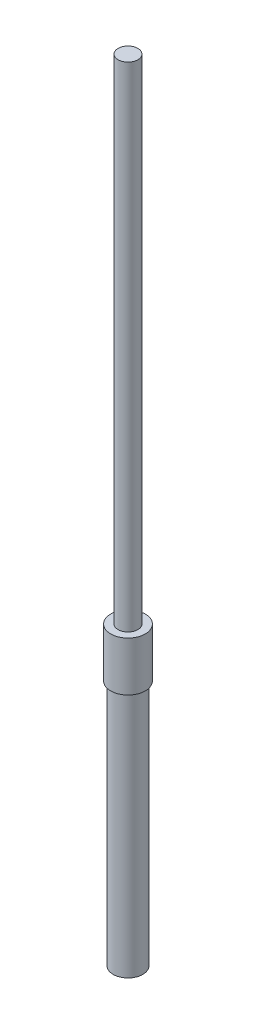
SolidWorks part; units mm, degrees
ref_plane "Front Plane" through (0, 0, 0) normal (0, 0, 1) x (1, 0, 0)
ref_plane "Top Plane" through (0, 0, 0) normal (0, 1, 0) x (1, 0, 0)
ref_plane "Right Plane" through (0, 0, 0) normal (1, 0, 0) x (0, 0, -1)
other "Configuration Table"
sketch "Sketch1" plane through (0, 0, 0) normal (0, 1, 0) x (1, 0, 0)
  circle A0 centre (0, 0) radius 3
  dimension "D1" = 6
extrude "Steel_Tube" add sketch "Sketch1" along normal blind 50
sketch "Sketch2" plane through (0, 0, 0) normal (0, 1, 0) x (1, 0, 0)
  circle A0 centre (0, 0) radius 3.5
extrude "Heatshrink" add sketch "Sketch2" along normal blind 10 from offset 50
sketch "Sketch3" plane through (0, 0, 0) normal (0, 1, 0) x (1, 0, 0)
  circle A0 centre (0, 0) radius 2
extrude "Cable" add sketch "Sketch3" along normal blind 100 from offset 60
equation "\"ds_D\"= 6.0   'ASSUMPTION: DS18B20 steel tube OD (PDF fallback)"
equation "\"ds_L\"= 50.0   'ASSUMPTION: DS18B20 steel tube length (PDF fallback)"
equation "\"cable_D\"= 4.0   'ASSUMPTION: Probe cable OD (designer choice)"
equation "\"D1@Sketch1\" = \"ds_D\""
equation "\"D1@Steel_Tube\" = \"ds_L\""
